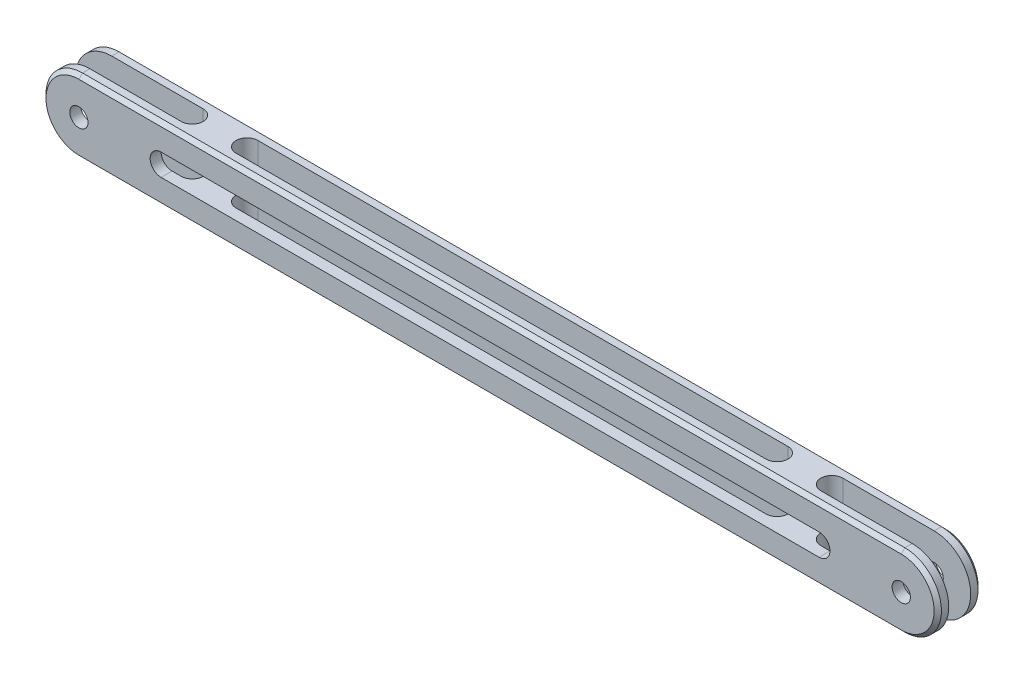
SolidWorks part; units mm, degrees
ref_plane "Front Plane" through (0, 0, 0) normal (0, 0, 1) x (1, 0, 0)
ref_plane "Top Plane" through (0, 0, 0) normal (0, 1, 0) x (1, 0, 0)
ref_plane "Right Plane" through (0, 0, 0) normal (1, 0, 0) x (0, 0, -1)
sketch "Sketch2" plane through (0, 0, 0) normal (0, 0, 1) x (1, 0, 0)
  line L0 (-112.5, 0) -> (112.5, 0) construction
  line L2 (-112.5, 10) -> (112.5, 10)
  line L3 (-112.5, -10) -> (112.5, -10)
  arc A0 (-112.5, 10) -> (-112.5, -10) centre (-112.5, 0) ccw
  arc A1 (112.5, -10) -> (112.5, 10) centre (112.5, 0) ccw
  point P5 (0, 0)
  dimension "D1" = 10
  dimension "D2" = 225
extrude "Boss-Extrude1" add sketch "Sketch2" against normal mid plane 12
sketch "Sketch3" plane through (0, 0, 0) normal (0, 1, 0) x (1, 0, 0)
  line L0 (-72.5, 0) -> (72.5, 0) construction
  line L1 (157.5, 0) -> (87.5, 0) construction
  line L2 (-72.5, 3) -> (72.5, 3)
  line L3 (-72.5, -3) -> (72.5, -3)
  line L4 (122.5, -6) -> (122.5, 6) construction
  line L5 (157.5, -3) -> (87.5, -3)
  line L6 (157.5, 3) -> (87.5, 3)
  line L7 (0, 0) -> (0, -18.0305) construction
  line L8 (-157.5, 0) -> (-87.5, 0) construction
  line L9 (-157.5, -3) -> (-87.5, -3)
  line L10 (-157.5, 3) -> (-87.5, 3)
  arc A0 (-72.5, 3) -> (-72.5, -3) centre (-72.5, 0) ccw
  arc A1 (72.5, -3) -> (72.5, 3) centre (72.5, 0) ccw
  arc A2 (157.5, -3) -> (157.5, 3) centre (157.5, 0) ccw
  arc A3 (87.5, 3) -> (87.5, -3) centre (87.5, 0) ccw
  arc A4 (-157.5, -3) -> (-157.5, 3) centre (-157.5, 0) cw
  arc A5 (-87.5, 3) -> (-87.5, -3) centre (-87.5, 0) cw
  point P5 (0, 0)
  point P12 (122.5, 0)
  point P21 (-122.5, 0)
  dimension "D2" = 3
  dimension "D3" = 3
  dimension "D1" = 145
  dimension "D4" = 70
extrude "Cut-Extrude1" cut sketch "Sketch3" against normal mid plane 102
sketch "Sketch4" plane through (0, 0, 6) normal (0, 0, 1) x (1, 0, 0)
  line L0 (-90, 0) -> (90, 0) construction
  line L1 (-90, 3) -> (90, 3)
  line L2 (-90, -3) -> (90, -3)
  circle A0 centre (112.5, 0) radius 2.5
  circle A1 centre (-112.5, 0) radius 2.5
  arc A2 (-90, 3) -> (-90, -3) centre (-90, 0) ccw
  arc A3 (90, -3) -> (90, 3) centre (90, 0) ccw
  point P8 (0, 0)
  dimension "D1" = 5
  dimension "D2" = 5
  dimension "D4" = 3
  dimension "D3" = 180
  dimension "D5" = 0
extrude "Cut-Extrude2" cut sketch "Sketch4" against normal blind 102
chamfer "Chamfer1" distance 1 angle 45 8 edges at (0, -10, -6) (122.5, 0, -6) (-122.5, 0, -6) (0, 10, -6) (0, -10, 6) (122.5, 0, 6) (-122.5, 0, 6) (0, 10, 6)
